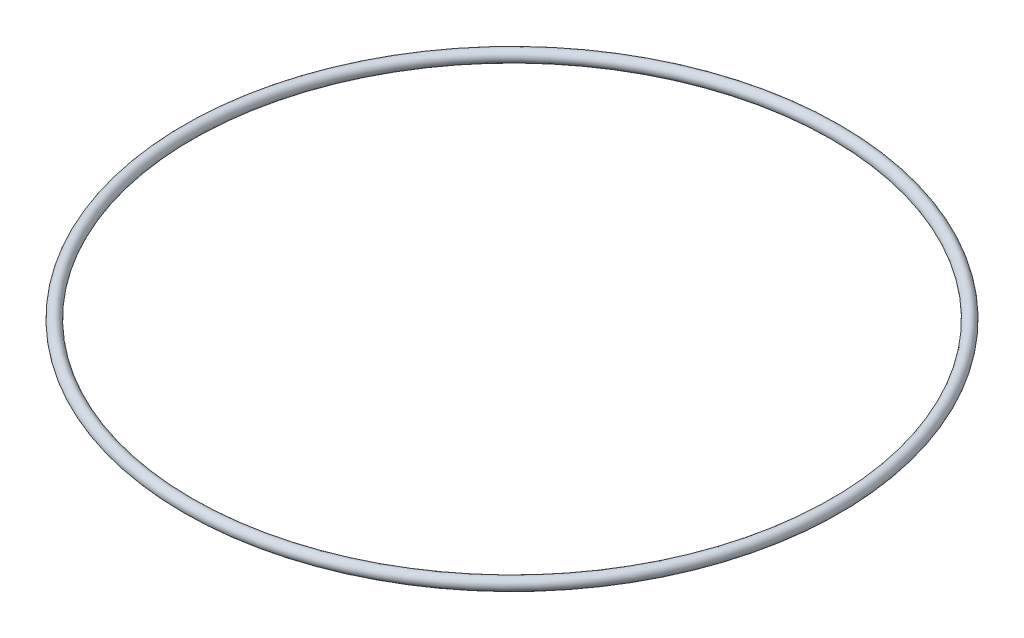
SolidWorks part; units mm, degrees
material "Nitinol"
ref_plane "Front Plane" through (0, 0, 0) normal (0, 0, 1) x (1, 0, 0)
ref_plane "Top Plane" through (0, 0, 0) normal (0, 1, 0) x (1, 0, 0)
ref_plane "Right Plane" through (0, 0, 0) normal (1, 0, 0) x (0, 0, -1)
sketch "Sketch1" plane through (0, 0, 0) normal (0, 1, 0) x (1, 0, 0)
  circle A0 centre (0, 0) radius 27.94
  point P4 (0, 0)
  dimension "D1" = 55.88
sketch "Sketch2" plane through (0, 0, 0) normal (1, 0, 0) x (0, 0, -1)
  circle A0 centre (0, 0) radius 0.25
  dimension "D1" = 0.5
sweep "Sweep1" add path "Sketch1" circular profile diameter 1.016 parameters "D3"=1.016
